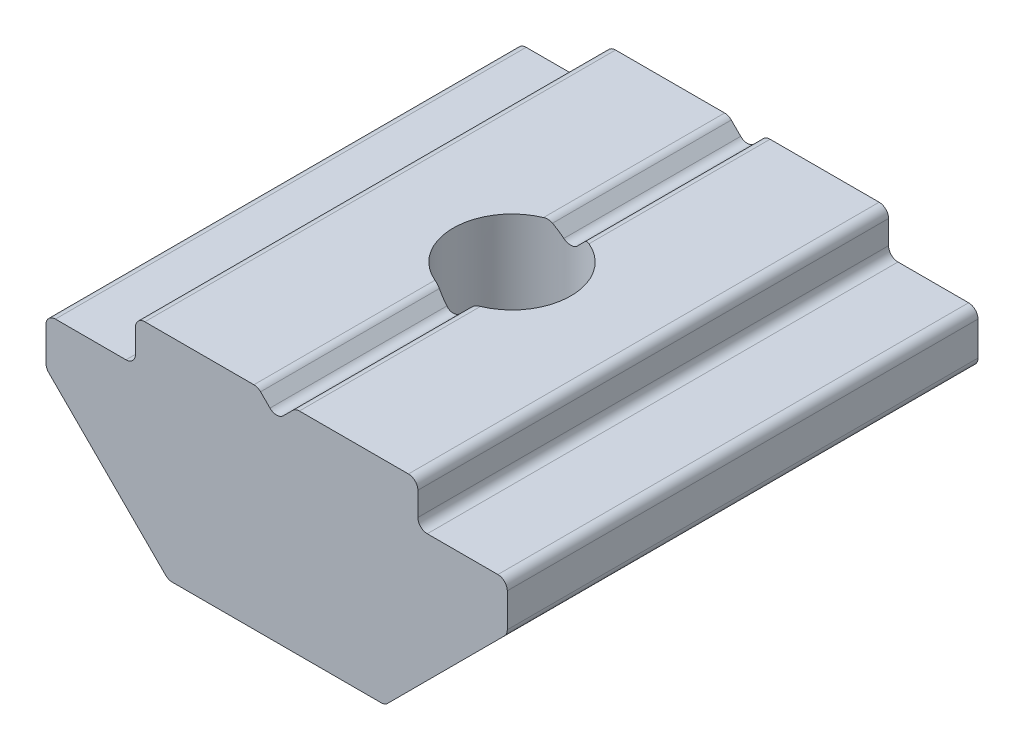
SolidWorks part; units mm, degrees
ref_plane "Front Plane" through (0, 0, 0) normal (0, 0, 1) x (1, 0, 0)
ref_plane "Top Plane" through (0, 0, 0) normal (0, 1, 0) x (1, 0, 0)
ref_plane "Right Plane" through (0, 0, 0) normal (1, 0, 0) x (0, 0, -1)
ref_plane "Plane1" through (0, 0, 5) normal (0, 0, 1) x (1, 0, 0)
sketch "Sketch1" plane through (0, 0, 5) normal (0, 0, 1) x (1, 0, 0)
  line L0 (4.9, -1) -> (4.9, 0.9)
  line L1 (4.9, 0.9) -> (-4.9, 0.9)
  line L2 (-4.9, 0.9) -> (-4.9, -1)
  line L3 (-4.9, -1) -> (-2.3, -3.6)
  line L4 (-2.3, -3.6) -> (2.3, -3.6)
  line L5 (2.3, -3.6) -> (4.9, -1)
extrude "Boss-Extrude1" add sketch "Sketch1" against normal blind 10
sketch "Sketch2" plane through (0, 0, -5) normal (0, 0, -1) x (-1, 0, 0)
  line L0 (4.9, 0.9) -> (3, 0.9)
  line L1 (3, 0.9) -> (3, 0)
  line L2 (3, 0) -> (4.9, 0)
  line L3 (4.9, 0) -> (4.9, 0.9)
extrude "Cut-Extrude1" cut sketch "Sketch2" against normal through all
sketch "Sketch3" plane through (0, 0, -5) normal (0, 0, -1) x (-1, 0, 0)
  line L0 (-4.9, 0) -> (-3, 0)
  line L1 (-3, 0) -> (-3, 0.9)
  line L2 (-3, 0.9) -> (-4.9, 0.9)
  line L3 (-4.9, 0.9) -> (-4.9, 0)
extrude "Cut-Extrude2" cut sketch "Sketch3" against normal through all
sketch "Sketch4" plane through (0, 0, -5) normal (0, 0, -1) x (-1, 0, 0)
  line L0 (0.4, 0.9) -> (-0.4, 0.9)
  line L1 (-0.4, 0.9) -> (0, 0.5)
  line L2 (0, 0.5) -> (0.4, 0.9)
extrude "Cut-Extrude3" cut sketch "Sketch4" against normal through all
hole_wizard "Ø4.2 (4.2) Diameter Hole1" positions "Sketch6" profile "Sketch5" hole size "Ø4.2" standard "ANSI Metric"
sketch "Sketch6" plane through (0, -3.6, 0) normal (0, -1, 0) x (-1, 0, 0)
  point P0 (0, 0)
sketch "Sketch5" plane through (0, -3.6, 0) normal (1, 0, 0) x (0, 0, -1)
  line L0 (0, 0) -> (0, 4.5)
  line L1 (0, 4.5) -> (1.25, 4.5)
  line L2 (1.25, 4.5) -> (1.25, 0)
  line L5 (1.25, 0) -> (0, 0)
  line L11 (0, -6.35) -> (0, 107.95) construction
  dimension "Thru Hole Dia." = 2.5
  dimension "Thru Hole Depth" = 4.5
fillet "Fillet1" radius 0.2 16 edges at (4.9, 0, 0) (3, 0, 0) (-4.9, -1, 0) (3, 0.9, 0) (-3, 0, 0) (0.4, 0.9, -3.0921) (0, 0.5, 3.125) (-0.4, 0.9, -3.0921) (4.9, -1, 0) (-3, 0.9, 0) (0, 0.5, -3.125) (-0.4, 0.9, 3.0921) (-4.9, 0, 0) (-2.3, -3.6, 0) (0.4, 0.9, 3.0921) (2.3, -3.6, 0)
